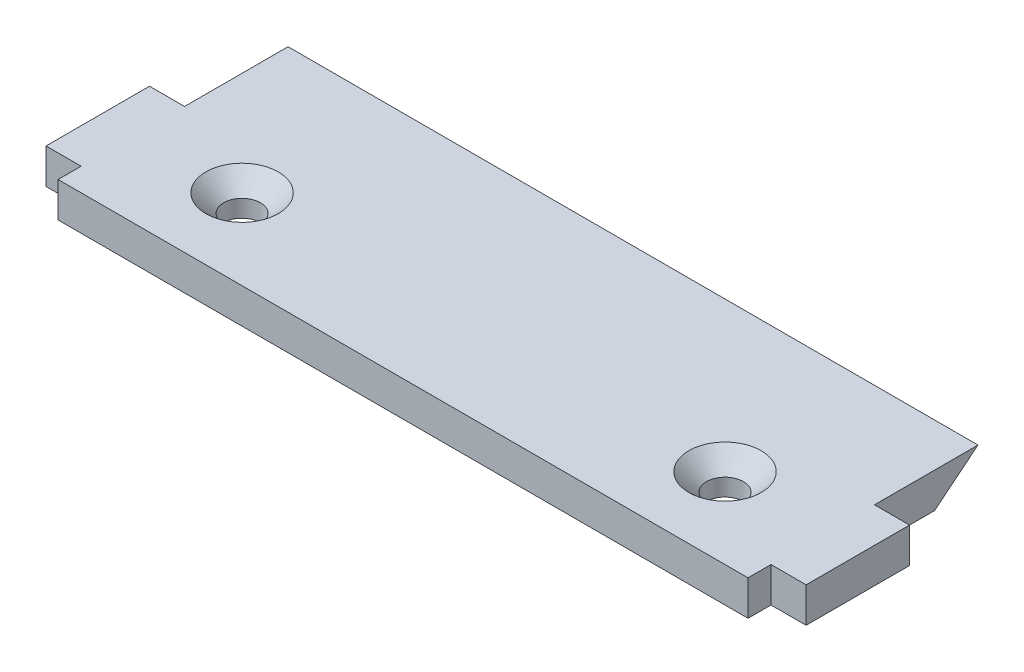
SolidWorks part; units mm, degrees
ref_plane "Front Plane" through (0, 0, 0) normal (0, 0, 1) x (1, 0, 0)
ref_plane "Top Plane" through (0, 0, 0) normal (0, 1, 0) x (1, 0, 0)
ref_plane "Right Plane" through (0, 0, 0) normal (1, 0, 0) x (0, 0, -1)
sketch "Sketch1" plane through (0, 0, 0) normal (0, 1, 0) x (1, 0, 0)
  line L1 (0, 0) -> (66.1, 0)
  line L2 (0, 0) -> (0, 20)
  line L3 (0, 20) -> (66.1, 20)
  line L4 (66.1, 0) -> (66.1, 20)
  line L7 (0, 11) -> (3.05, 11)
  line L8 (3.05, 20) -> (3.05, 11)
  line L11 (66.1, 11) -> (63.05, 11)
  line L12 (63.05, 20) -> (63.05, 11)
  line L13 (0, 0) -> (12.05, 0)
  line L14 (0, 0) -> (0, 7)
  line L15 (0, 7) -> (12.05, 7)
  line L16 (12.05, 0) -> (12.05, 7)
  line L17 (66.1, 0) -> (54.05, 0)
  line L18 (66.1, 0) -> (66.1, 7)
  line L19 (66.1, 7) -> (54.05, 7)
  line L20 (54.05, 0) -> (54.05, 7)
  line L23 (66.1, 0) -> (63.05, 0)
  line L24 (66.1, 0) -> (66.1, 2)
  line L25 (66.1, 2) -> (63.05, 2)
  line L26 (63.05, 0) -> (63.05, 2)
  line L27 (0, 0) -> (3.05, 0)
  line L28 (0, 0) -> (0, 2)
  line L29 (0, 2) -> (3.05, 2)
  line L30 (3.05, 0) -> (3.05, 2)
  circle A0 centre (12.05, 7) radius 1.5
  circle A1 centre (54.05, 7) radius 1.5
  dimension "D9" = 3
  dimension "D12" = 3
  dimension "D1" = 20
  dimension "D2" = 66.1
  dimension "D4" = 3.05
  dimension "D6" = 3.05
  dimension "D7" = 12.05
  dimension "D8" = 7
  dimension "D10" = 7
  dimension "D11" = 12.05
  dimension "D13" = 4
  dimension "D15" = 4
  dimension "D17" = 2
  dimension "D18" = 3.05
  dimension "D19" = 2
  dimension "D20" = 3.05
extrude "Boss-Extrude1" add sketch "Sketch1" along normal blind 3.05 contours A1 L19 L4 L11 L12 L3 L8 L7 L2 L15 A0 L16 L1 L20 | A0 L15 L14 L29 L30 L13 L16 | A1 L20 L1 L26 L25 L18 L19
hole_wizard "CSK for M3 Flat Head Machine Screw1" positions "Sketch4" profile "Sketch5" countersink size "M3" standard "ANSI Metric" end condition through all
sketch "Sketch4" plane through (0, 3.05, 0) normal (0, 1, 0) x (1, 0, 0)
  point P0 (12.05, 7)
sketch "Sketch5" plane through (12.05, 3.05, -7) normal (1, 0, 0) x (0, 0, 1)
  line L0 (0, 0) -> (0, 3.05)
  line L1 (0, 3.05) -> (1.6, 3.05)
  line L2 (1.6, 3.05) -> (1.6, 1.55)
  line L3 (1.6, 1.55) -> (3.15, 0)
  line L5 (3.15, 0) -> (0, 0)
  line L6 (-1.6, 1.55) -> (-3.15, 0) construction
  line L11 (0, -6.35) -> (0, 107.95) construction
  dimension "Thru Hole Dia." = 3.2
  dimension "Thru Hole Depth" = 3.05
  dimension "Near C'Sink Dia." = 6.3
  dimension "Near C'Sink Angle" = 90
hole_wizard "CSK for M3 Flat Head Machine Screw2" positions "Sketch6" profile "Sketch7" countersink size "M3" standard "ANSI Metric" end condition through all
sketch "Sketch6" plane through (0, 3.05, 0) normal (0, 1, 0) x (1, 0, 0)
  point P0 (54.05, 7)
sketch "Sketch7" plane through (54.05, 3.05, -7) normal (1, 0, 0) x (0, 0, 1)
  line L0 (0, 0) -> (0, 3.05)
  line L1 (0, 3.05) -> (1.6, 3.05)
  line L2 (1.6, 3.05) -> (1.6, 1.55)
  line L3 (1.6, 1.55) -> (3.15, 0)
  line L5 (3.15, 0) -> (0, 0)
  line L6 (-1.6, 1.55) -> (-3.15, 0) construction
  line L11 (0, -6.35) -> (0, 107.95) construction
  dimension "Thru Hole Dia." = 3.2
  dimension "Thru Hole Depth" = 3.05
  dimension "Near C'Sink Dia." = 6.3
  dimension "Near C'Sink Angle" = 90
sketch "Sketch8" plane through (3.05, 0, 0) normal (-1, 0, 0) x (0, 0, 1)
  line L0 (-20, 0) -> (-20, 3.05)
  line L1 (-20, 3.05) -> (-16.2238, 0)
  line L3 (-20, 0) -> (-11, 0) construction
  line L4 (-16.2238, 0) -> (-20, 0)
  dimension "D1" = 38.928
extrude "Cut-Extrude1" cut sketch "Sketch8" against normal through all
